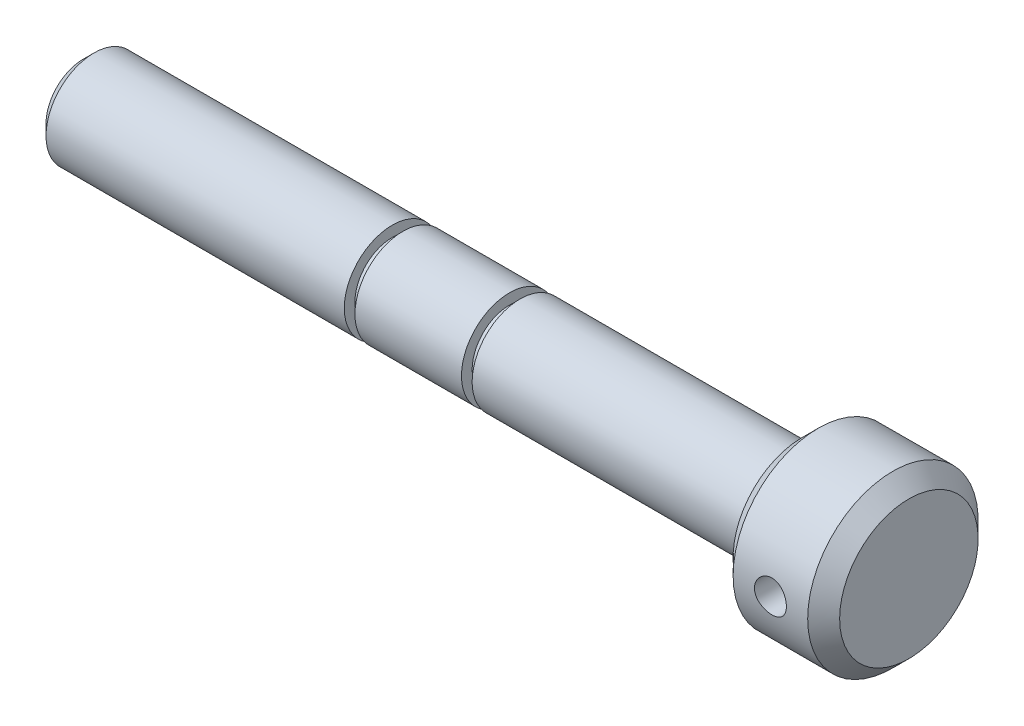
SolidWorks part; units mm, degrees
ref_plane "Front Plane" through (0, 0, 0) normal (0, 0, 1) x (1, 0, 0)
ref_plane "Top Plane" through (0, 0, 0) normal (0, 1, 0) x (1, 0, 0)
ref_plane "Right Plane" through (0, 0, 0) normal (1, 0, 0) x (0, 0, -1)
sketch "Sketch1" plane through (0, 0, 0) normal (0, 0, 1) x (1, 0, 0)
  line L0 (0, 0) -> (155, 0) construction
  line L1 (155, 0) -> (155, 16)
  line L2 (155, 16) -> (135, 16)
  line L3 (135, 16) -> (135, 9)
  line L4 (135, 9) -> (82, 9)
  line L5 (82, 9) -> (82, 7)
  line L6 (82, 7) -> (80, 7)
  line L7 (80, 7) -> (80, 9)
  line L8 (80, 9) -> (60, 9)
  line L9 (60, 9) -> (60, 7)
  line L10 (60, 7) -> (58, 7)
  line L11 (58, 7) -> (58, 9)
  line L12 (58, 9) -> (0, 9)
  line L13 (0, 9) -> (0, 0)
  line L14 (0, 0) -> (155, 0)
  dimension "D1" = 155
  dimension "D2" = 16
  dimension "D3" = 20
  dimension "D4" = 7
  dimension "D5" = 2
  dimension "D6" = 53
  dimension "D7" = 20
  dimension "D8" = 2
  dimension "D9" = 9
  dimension "D10" = 9
  dimension "D11" = 9
  dimension "D12" = 7
revolve "Revolve1" add sketch "Sketch1" angle 360 about L0
cosmetic thread "Cosmetic Thread2" parameters "D2"=16.344
chamfer "Chamfer1" distance 3 angle 45 2 edges at (135, 0, 16) (155, 0, 16)
chamfer "Chamfer2" distance 2 angle 45 1 edges at (0, 0, 9)
cosmetic thread "Cosmetic Thread1" parameters "D2"=16.344
sketch "Sketch2" plane through (0, 0, 0) normal (0, 0, 1) x (1, 0, 0)
  line L1 (155, -13) -> (155, 13) construction
  circle A0 centre (145, 0) radius 3
  dimension "D1" = 6
  dimension "D2" = 10
extrude "Boss-Extrude1" add sketch "Sketch2" along normal mid plane 10 contours A0
sketch "Sketch3" plane through (0, 0, 0) normal (0, 0, 1) x (1, 0, 0)
  line L0 (155, -13) -> (155, 13) construction
  circle A0 centre (145, 0) radius 3
  dimension "D1" = 6
  dimension "D2" = 10
extrude "Cut-Extrude1" cut sketch "Sketch3" against normal mid plane 400
